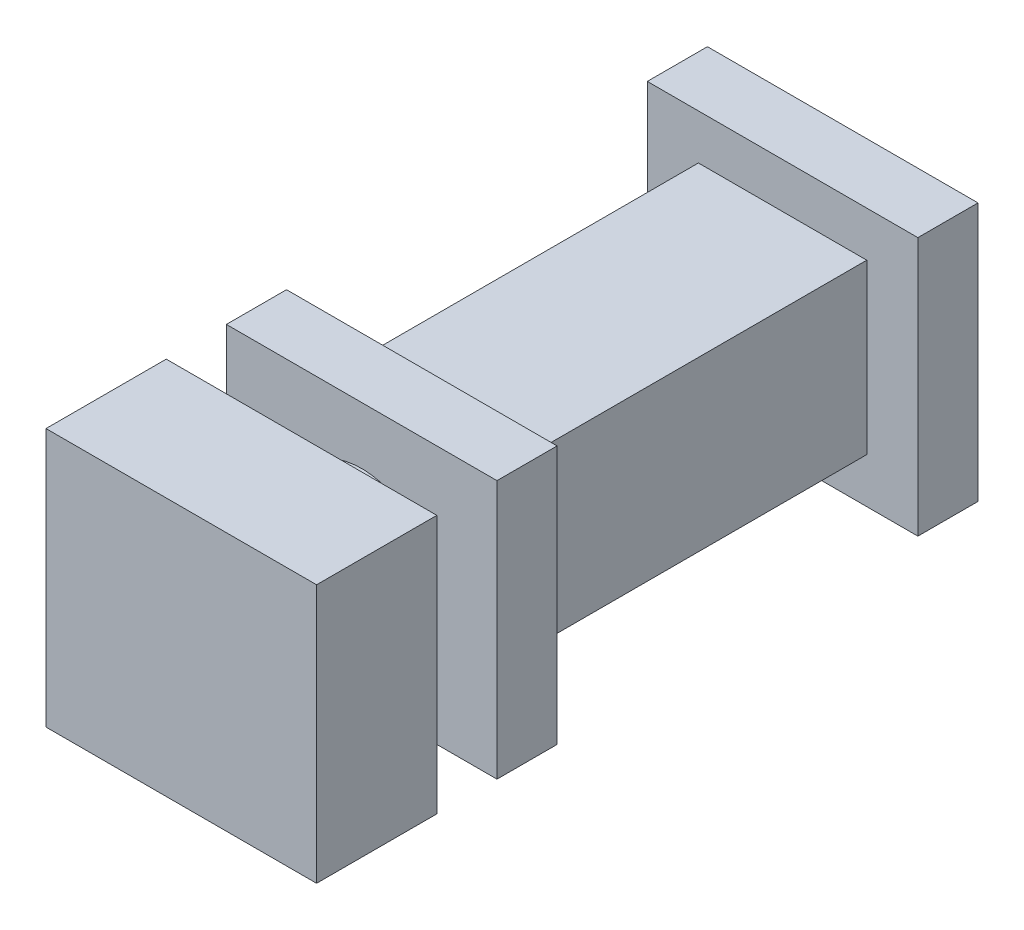
SolidWorks part; units mm, degrees
ref_plane "前视基准面" through (0, 0, 0) normal (0, 0, 1) x (1, 0, 0)
ref_plane "上视基准面" through (0, 0, 0) normal (0, 1, 0) x (1, 0, 0)
ref_plane "右视基准面" through (0, 0, 0) normal (1, 0, 0) x (0, 0, -1)
sketch "草图2" plane through (0, 0, 0) normal (0, 0, 1) x (1, 0, 0)
  line L9 (-1.125, -1.075) -> (1.125, -1.075)
  line L10 (-1.125, -1.075) -> (-1.125, 1.075)
  line L11 (-1.125, 1.075) -> (1.125, 1.075)
  line L12 (1.125, -1.075) -> (1.125, 1.075)
  line L13 (-1.125, -1.075) -> (1.125, 1.075) construction
  line L14 (-1.125, 1.075) -> (1.125, -1.075) construction
  point P0 (0, 0)
  dimension "D1" = 2.15
  dimension "D2" = 2.25
extrude "凸台-拉伸4" add sketch "草图2" along normal blind 1
sketch "草图4" plane through (0, 0, 0) normal (0, 0, -1) x (-1, 0, 0)
  circle A0 centre (0, 0) radius 0.6
  dimension "D1" = 1.2
extrude "凸台-拉伸5" add sketch "草图4" along normal blind 0.5
sketch "草图5" plane through (0, 0, -0.5) normal (0, 0, -1) x (-1, 0, 0)
  line L1 (-1.125, -1.075) -> (1.125, -1.075)
  line L2 (-1.125, -1.075) -> (-1.125, 1.075)
  line L3 (-1.125, 1.075) -> (1.125, 1.075)
  line L4 (1.125, -1.075) -> (1.125, 1.075)
  line L5 (-1.125, -1.075) -> (1.125, 1.075) construction
  line L6 (-1.125, 1.075) -> (1.125, -1.075) construction
  point P0 (0, 0)
  dimension "D1" = 2.15
  dimension "D2" = 2.25
extrude "凸台-拉伸6" add sketch "草图5" along normal blind 0.5
sketch "草图9" plane through (0, 0, -1) normal (0, 0, -1) x (-1, 0, 0)
  line L1 (-0.7, -0.7) -> (0.7, -0.7)
  line L2 (-0.7, -0.7) -> (-0.7, 0.7)
  line L3 (-0.7, 0.7) -> (0.7, 0.7)
  line L4 (0.7, -0.7) -> (0.7, 0.7)
  line L5 (-0.7, -0.7) -> (0.7, 0.7) construction
  line L6 (-0.7, 0.7) -> (0.7, -0.7) construction
  point P0 (0, 0)
  dimension "D1" = 1.4
extrude "凸台-拉伸7" add sketch "草图9" along normal blind 3
sketch "草图10" plane through (0, 0, -4) normal (0, 0, -1) x (-1, 0, 0)
  line L1 (-1.125, -1.075) -> (1.125, -1.075)
  line L2 (-1.125, -1.075) -> (-1.125, 1.075)
  line L3 (-1.125, 1.075) -> (1.125, 1.075)
  line L4 (1.125, -1.075) -> (1.125, 1.075)
  line L5 (-1.125, -1.075) -> (1.125, 1.075) construction
  line L6 (-1.125, 1.075) -> (1.125, -1.075) construction
  point P0 (0, 0)
extrude "凸台-拉伸8" add sketch "草图10" along normal blind 0.5
